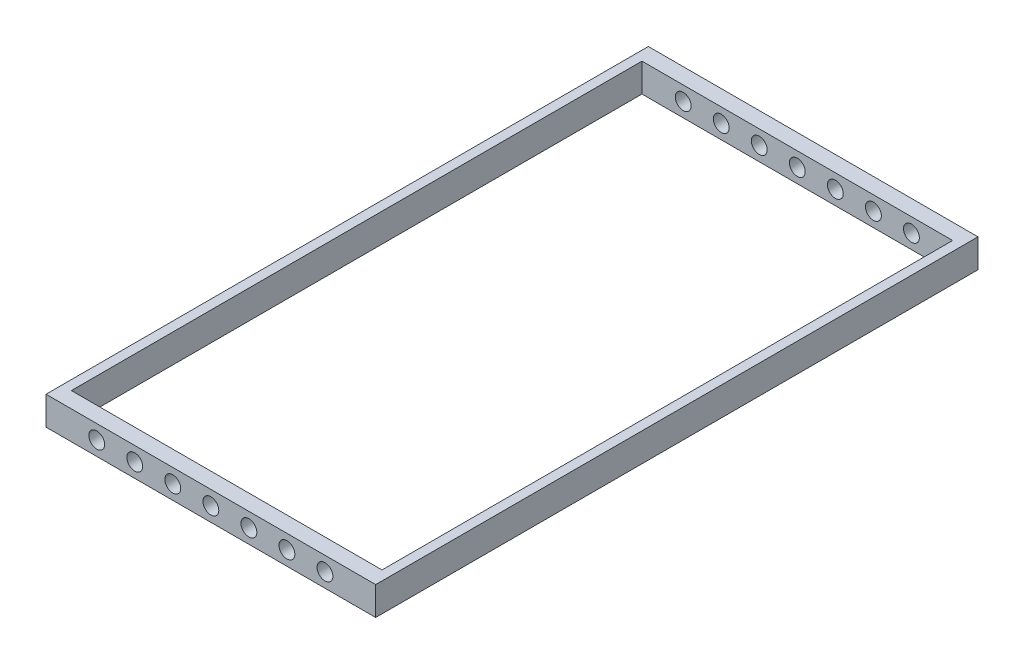
SolidWorks part; units mm, degrees
ref_plane "前基準面" through (0, 0, 0) normal (0, 0, 1) x (1, 0, 0)
ref_plane "上基準面" through (0, 0, 0) normal (0, 1, 0) x (1, 0, 0)
ref_plane "右基準面" through (0, 0, 0) normal (1, 0, 0) x (0, 0, -1)
sketch "草圖1" plane through (0, 0, 0) normal (0, 0, 1) x (1, 0, 0)
  line L0 (-36, 0) -> (-52, 0) construction
  line L1 (-52, 4.5) -> (52, 4.5)
  line L2 (-52, 4.5) -> (-52, -4.5)
  line L3 (-52, -4.5) -> (52, -4.5)
  line L4 (52, 4.5) -> (52, -4.5)
  line L5 (-52, 4.5) -> (52, -4.5) construction
  line L6 (-52, -4.5) -> (52, 4.5) construction
  line L7 (36, 0) -> (52, 0) construction
  line L8 (52, 0) -> (36, 0) construction
  circle A0 centre (-36, 0) radius 2.5
  circle A1 centre (-24, 0) radius 2.5
  circle A2 centre (-12, 0) radius 2.5
  circle A3 centre (0, 0) radius 2.5
  circle A4 centre (12, 0) radius 2.5
  circle A5 centre (24, 0) radius 2.5
  circle A6 centre (36, 0) radius 2.5
  point P0 (0, 0)
  dimension "D1" = 5
  dimension "D4" = 9
  dimension "D2" = 7
  dimension "D3" = 104
extrude "填料-伸長1" add sketch "草圖1" along normal blind 5
sketch "草圖2" plane through (0, 0, 0) normal (0, 0, -1) x (-1, 0, 0)
  line L0 (52, -4.5) -> (-52, -4.5) construction
  line L1 (-52, 4.5) -> (-49, 4.5)
  line L2 (-52, 4.5) -> (-52, -4.5)
  line L3 (-52, -4.5) -> (-49, -4.5)
  line L4 (-49, 4.5) -> (-49, -4.5)
  line L6 (52, 4.5) -> (49, 4.5)
  line L7 (52, 4.5) -> (52, -4.5)
  line L8 (52, -4.5) -> (49, -4.5)
  line L9 (49, 4.5) -> (49, -4.5)
  dimension "D1" = 3
extrude "填料-伸長2" add sketch "草圖2" along normal blind 90
mirror "鏡射4" about plane through (0, 0, -90) normal (0, 0, -1) of "填料-伸長1", "填料-伸長2"
